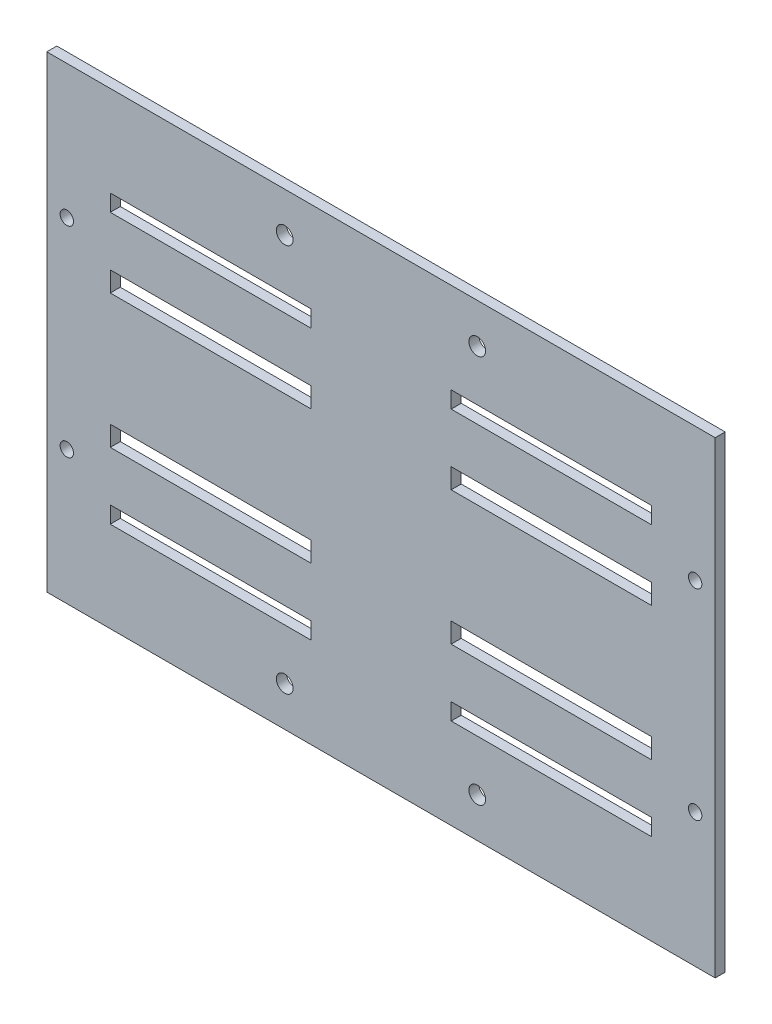
SolidWorks part; units mm, degrees
ref_plane "Front" through (0, 0, 0) normal (0, 0, 1) x (1, 0, 0)
ref_plane "Top" through (0, 0, 0) normal (0, 1, 0) x (1, 0, 0)
ref_plane "Right" through (0, 0, 0) normal (1, 0, 0) x (0, 0, -1)
sketch "草图2" plane through (0, 0, 0) normal (0, 0, 1) x (1, 0, 0)
  line L1 (-100, -70) -> (100, -70)
  line L2 (-100, -70) -> (-100, 70)
  line L3 (-100, 70) -> (100, 70)
  line L4 (100, -70) -> (100, 70)
  line L5 (-100, -70) -> (100, 70) construction
  line L6 (-100, 70) -> (100, -70) construction
  point P0 (0, 0)
  dimension "D1" = 140
  dimension "D2" = 200
extrude "凸台-拉伸1" add sketch "草图2" along normal blind 3
sketch "草图3" plane through (0, 0, 3) normal (0, 0, 1) x (1, 0, 0)
  line L0 (94, -30) -> (94, 30) construction
  line L2 (100, -70) -> (100, 70) construction
  circle A0 centre (94, 30) radius 2
  circle A1 centre (94, -30) radius 2
  point P4 (94, 0)
  dimension "D1" = 4
  dimension "D2" = 60
  dimension "D3" = 6
extrude "切除-拉伸1" cut sketch "草图3" against normal blind 3 contours A0 | A1
sketch "草图4" plane through (0, 0, 3) normal (0, 0, 1) x (1, 0, 0)
  line L0 (-100, 0) -> (100, 0) construction
  line L1 (-100, 70) -> (-100, -70) construction
  line L2 (100, -70) -> (100, 70) construction
  line L4 (21, 23) -> (81, 23)
  line L5 (21, 23) -> (21, 17)
  line L6 (21, 17) -> (81, 17)
  line L7 (81, 23) -> (81, 17)
  line L8 (21, 23) -> (81, 17) construction
  line L9 (21, 17) -> (81, 23) construction
  line L10 (21, -23) -> (81, -23)
  line L11 (21, -23) -> (21, -17)
  line L12 (21, -17) -> (81, -17)
  line L13 (81, -23) -> (81, -17)
  line L14 (21, -23) -> (81, -17) construction
  line L15 (21, -17) -> (81, -23) construction
  point P6 (51, 20)
  point P11 (51, -20)
  dimension "D1" = 34
  dimension "D2" = 6
  dimension "D3" = 6
  dimension "D4" = 17
  dimension "D5" = 60
  dimension "D6" = 19
extrude "切除-拉伸2" cut sketch "草图4" against normal blind 10
sketch "草图5" plane through (0, 0, 0) normal (0, 0, -1) x (-1, 0, 0)
  line L0 (-21, 17) -> (-21, 23) construction
  line L1 (-81, 37.9088) -> (-21, 37.9088)
  line L2 (-81, 37.9088) -> (-81, 42.9088)
  line L3 (-81, 42.9088) -> (-21, 42.9088)
  line L4 (-21, 37.9088) -> (-21, 42.9088)
  line L5 (-81, 37.9088) -> (-21, 42.9088) construction
  line L6 (-81, 42.9088) -> (-21, 37.9088) construction
  line L7 (-81, 23) -> (-81, 17) construction
  point P0 (-51, 40.4088)
  dimension "D1" = 5
extrude "切除-拉伸3" cut sketch "草图5" against normal blind 6
mirror "镜向1" about plane through (0, 0, 0) normal (0, 1, 0) of "切除-拉伸3"
ref_plane "基准面1" through (0, 0, 0) normal (-1, 0, 0) x (0, 0, 1)
mirror "镜向2" about plane through (0, 0, 0) normal (-1, 0, 0) of "切除-拉伸1", "镜向1", "切除-拉伸2", "切除-拉伸3"
sketch "草图6" plane through (0, 0, 3) normal (0, 0, 1) x (1, 0, 0)
  circle A0 centre (-28.8, 58.1086) radius 2.5 construction
  circle A1 centre (-28.8, 58.1086) radius 2.5
  circle A2 centre (-28.8, -58.1086) radius 2.5 construction
  circle A3 centre (28.8, -58.1086) radius 2.5 construction
  circle A4 centre (28.8, 58.1086) radius 2.5 construction
  circle A5 centre (-28.8, -58.1086) radius 2.5
  circle A6 centre (28.8, -58.1086) radius 2.5
  circle A7 centre (28.8, 58.1086) radius 2.5
extrude "切除-拉伸4" cut sketch "草图6" against normal blind 5
